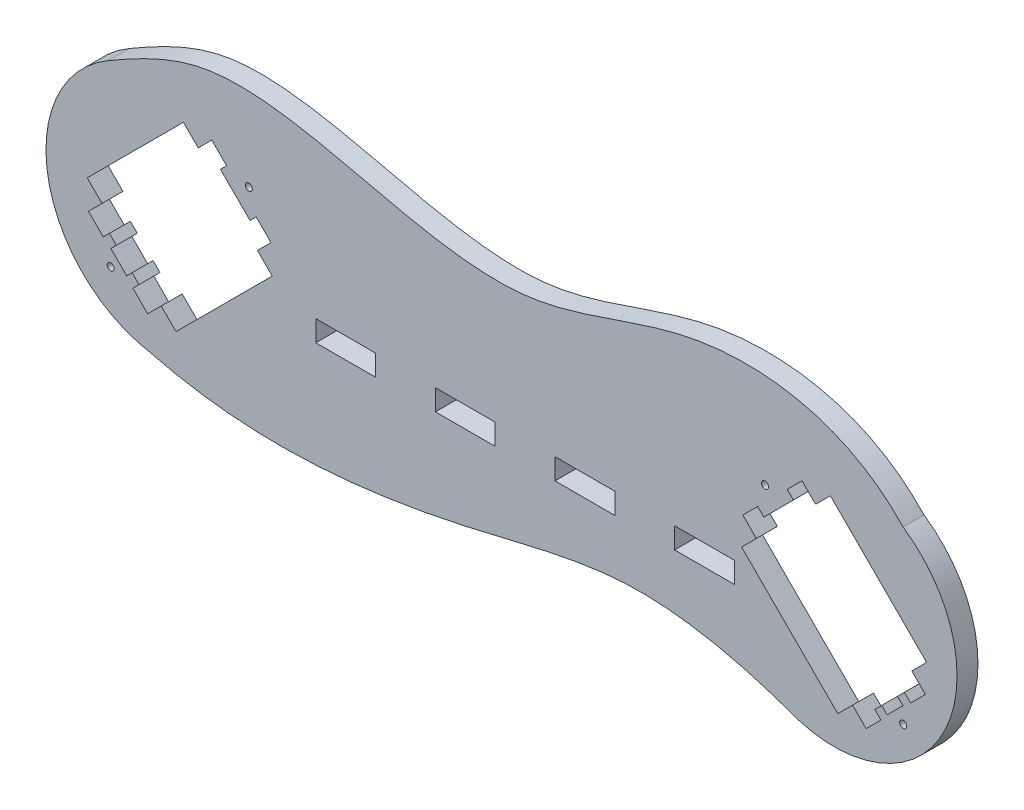
SolidWorks part; units mm, degrees
ref_plane "Ebene vorne" through (0, 0, 0) normal (0, 0, 1) x (1, 0, 0)
ref_plane "Ebene oben" through (0, 0, 0) normal (0, 1, 0) x (1, 0, 0)
ref_plane "Ebene rechts" through (0, 0, 0) normal (1, 0, 0) x (0, 0, -1)
sketch "Skizze1" plane through (0, 0, 0) normal (0, 0, 1) x (1, 0, 0)
  line L0 (49.5015, -13.57) -> (33.5916, 2.3399)
  line L1 (49.5015, -13.57) -> (57.9868, -5.0848)
  line L2 (33.5916, 2.3399) -> (42.0769, 10.8252)
  line L3 (57.9868, -5.0848) -> (42.0769, 10.8252)
  line L4 (-51.7123, -13.57) -> (-35.8024, 2.3399)
  line L5 (-51.7123, -13.57) -> (-60.1976, -5.0848)
  line L6 (-35.8024, 2.3399) -> (-44.2877, 10.8252)
  line L7 (-60.1976, -5.0848) -> (-44.2877, 10.8252)
  line L8 (-48, -1.3724) -> (45.7892, -1.3724) construction
  line L16 (-44.2877, 10.8252) -> (-51.7123, -13.57) construction
  line L17 (42.0769, 10.8252) -> (49.5015, -13.57) construction
  line L18 (-49.2108, -1.3724) -> (45.7892, -1.3724) construction
  arc A3 (39.0938, -17.6773) -> (55.6749, 13.2203) centre (45.7892, -1.3724) ccw
  arc A6 (-58.2694, 14.1365) -> (-52.2522, -19.0737) centre (-49.2108, -1.3724) ccw
  spline S2 degree 3 poles (39.0938, -17.6773) (32.2117, -15.2613) (16.8741, -11.709) (-13.1309, -20.3405) (-36.8406, -23.0582) (-52.2522, -19.0737) knots 0 0 0 0 0.240413 0.489928 1 1 1 1
  spline S3 degree 3 poles (55.6749, 13.2203) (47.6095, 21.8182) (26.7795, 24.966) (-4.8193, 8.388) (-36.1432, 25.5157) (-52.9982, 17.2153) (-58.2694, 14.1365) knots 0 0 0 0 0.281767 0.483095 0.8718 1 1 1 1
  dimension "D9" = 17.9606
  dimension "D1" = 12
  dimension "D2" = 22.5
  dimension "D3" = 73.072
  dimension "D4" = 73.072
  dimension "D5" = 45.7892
  dimension "D6" = 1.3724
  dimension "D7" = 49.2108
  dimension "D8" = 48
extrude "Aufsatz-Linear austragen1" add sketch "Skizze1" along normal blind 3
sketch "Skizze3" plane through (0, 0, 3) normal (0, 0, 1) x (1, 0, 0)
  line L0 (-44.2877, 10.8252) -> (-60.1976, -5.0848) construction
  line L1 (33.5916, 2.3399) -> (49.5015, -13.57) construction
  line L2 (49.5015, -13.57) -> (57.9868, -5.0848) construction
  line L3 (-35.8024, 2.3399) -> (-44.2877, 10.8252) construction
  line B0 (-47.4697, 11.8858) -> (-61.2583, -1.9028)
  line B1 (-47.4697, 11.8858) -> (-45.3483, 9.7645)
  line B2 (-45.3483, 9.7645) -> (-43.4038, 11.709)
  line B3 (-43.4038, 11.709) -> (-41.2825, 9.5877)
  line B4 (-34.9185, 3.2238) -> (-36.8631, 1.2792)
  line B5 (-36.8631, 1.2792) -> (-34.7417, -0.8421)
  line B6 (-34.7417, -0.8421) -> (-48.5303, -14.6307)
  line B7 (-52.2426, 2.8702) -> (-43.7574, -5.6151) construction
  line B8 (-41.2825, 9.5877) -> (-42.1664, 8.7038)
  line B9 (-42.1664, 8.7038) -> (-37.9237, 4.4612)
  line B10 (-37.9237, 4.4612) -> (-37.0398, 5.3451)
  line B11 (-37.0398, 5.3451) -> (-34.9185, 3.2238)
  line B12 (-54.7175, -12.3326) -> (-52.5962, -14.4539)
  line B13 (-53.8336, -11.4487) -> (-54.7175, -12.3326)
  line B14 (-58.0763, -7.2061) -> (-53.8336, -11.4487)
  line B15 (-58.9602, -8.09) -> (-58.0763, -7.2061)
  line B16 (-50.6517, -12.5094) -> (-48.5303, -14.6307)
  line B17 (-52.5962, -14.4539) -> (-50.6517, -12.5094)
  line B18 (-61.0815, -5.9686) -> (-58.9602, -8.09)
  line B19 (-59.1369, -4.0241) -> (-61.0815, -5.9686)
  line B20 (-61.2583, -1.9028) -> (-59.1369, -4.0241)
  line B21 (59.0474, -1.9028) -> (45.2588, 11.8858)
  line B22 (59.0474, -1.9028) -> (56.9261, -4.0241)
  line B23 (56.9261, -4.0241) -> (58.8706, -5.9686)
  line B24 (58.8706, -5.9686) -> (56.7493, -8.09)
  line B25 (50.3854, -14.4539) -> (48.4408, -12.5094)
  line B26 (48.4408, -12.5094) -> (46.3195, -14.6307)
  line B27 (46.3195, -14.6307) -> (32.5309, -0.8421)
  line B28 (56.7493, -8.09) -> (55.8654, -7.2061)
  line B29 (55.8654, -7.2061) -> (51.6228, -11.4487)
  line B30 (51.6228, -11.4487) -> (52.5067, -12.3326)
  line B31 (52.5067, -12.3326) -> (50.3854, -14.4539)
  line B32 (34.829, 5.3451) -> (32.7077, 3.2238)
  line B33 (35.7129, 4.4612) -> (34.829, 5.3451)
  line B34 (39.9555, 8.7038) -> (35.7129, 4.4612)
  line B35 (39.0717, 9.5877) -> (39.9555, 8.7038)
  line B36 (34.6522, 1.2792) -> (32.5309, -0.8421)
  line B37 (32.7077, 3.2238) -> (34.6522, 1.2792)
  line B38 (41.193, 11.709) -> (39.0717, 9.5877)
  line B39 (43.1375, 9.7645) -> (41.193, 11.709)
  line B40 (45.2588, 11.8858) -> (43.1375, 9.7645)
sketch_block_instance "Block1-1"
sketch_block "Block1" parameters "D1"=19.5, "D2"=25, "D3"=3
sketch_block_instance "Block1-2"
extrude "Schnitt-Linear austragen2" cut sketch "Skizze3" against normal through all
hole_wizard "Ø1.0 (1) Durchmesser Bohrung1" positions "Skizze4" profile "Skizze5" hole size "Ø1.0" standard "DIN" end condition through all
sketch "Skizze4" plane through (0, 0, 3) normal (0, 0, 1) x (1, 0, 0)
  point P0 (-38.1005, 8.5271)
  point P3 (-57.8995, -11.2719)
  point P6 (35.8897, 8.5271)
  point P9 (55.6887, -11.2719)
sketch "Skizze5" plane through (-38.1005, 8.5271, 3) normal (1, 0, 0) x (0, -1, 0)
  line L0 (0, 0) -> (0, 3)
  line L1 (0, 3) -> (0.5, 3)
  line L2 (0.5, 3) -> (0.5, 0)
  line L5 (0.5, 0) -> (0, 0)
  line L11 (0, -6.35) -> (0, 107.95) construction
  dimension "Bohrerdurchmesser" = 1
  dimension "Bohrungstiefe" = 3
sketch "Skizze6" plane through (0, 0, 0) normal (0, 0, -1) x (-1, 0, 0)
  line L1 (-31.501, -3) -> (-22.9296, -3)
  line L2 (-31.501, -3) -> (-31.501, -6)
  line L3 (-31.501, -6) -> (-22.9296, -6)
  line L4 (-22.9296, -3) -> (-22.9296, -6)
  line L5 (-14.3582, -3) -> (-5.7868, -3)
  line L6 (-14.3582, -3) -> (-14.3582, -6)
  line L7 (-14.3582, -6) -> (-5.7868, -6)
  line L8 (-5.7868, -3) -> (-5.7868, -6)
  line L9 (2.7847, -3) -> (11.3561, -3)
  line L10 (2.7847, -3) -> (2.7847, -6)
  line L11 (2.7847, -6) -> (11.3561, -6)
  line L12 (11.3561, -3) -> (11.3561, -6)
  line L13 (19.9275, -3) -> (28.499, -3)
  line L14 (19.9275, -3) -> (19.9275, -6)
  line L15 (19.9275, -6) -> (28.499, -6)
  line L16 (28.499, -3) -> (28.499, -6)
extrude "Schnitt-Linear austragen3" cut sketch "Skizze6" against normal blind 10
sketch "Skizze7" plane through (0, 0, 3) normal (0, 0, 1) x (1, 0, 0)
  line L0 (-57.0863, -8.196) -> (-54.8236, -10.4588)
  line L1 (-57.0863, -8.196) -> (-57.8641, -8.9738)
  line L2 (-54.8236, -10.4588) -> (-55.6014, -11.2366)
  line L3 (-57.8641, -8.9738) -> (-55.6014, -11.2366)
  line L4 (-58.0763, -7.2061) -> (-53.8336, -11.4487) construction
  line L5 (52.6127, -10.4588) -> (54.8755, -8.196)
  line L6 (52.6127, -10.4588) -> (53.3906, -11.2366)
  line L7 (54.8755, -8.196) -> (55.6533, -8.9738)
  line L8 (53.3906, -11.2366) -> (55.6533, -8.9738)
  line L9 (51.6228, -11.4487) -> (55.8654, -7.2061) construction
  point P12 (53.7441, -9.3274)
  point P13 (53.7441, -9.3274)
  point P14 (-55.955, -9.3274)
  point P15 (-55.955, -9.3274)
  dimension "D1" = 1.1
  dimension "D2" = 3.2
extrude "Schnitt-Linear austragen4" cut sketch "Skizze7" against normal blind 10
